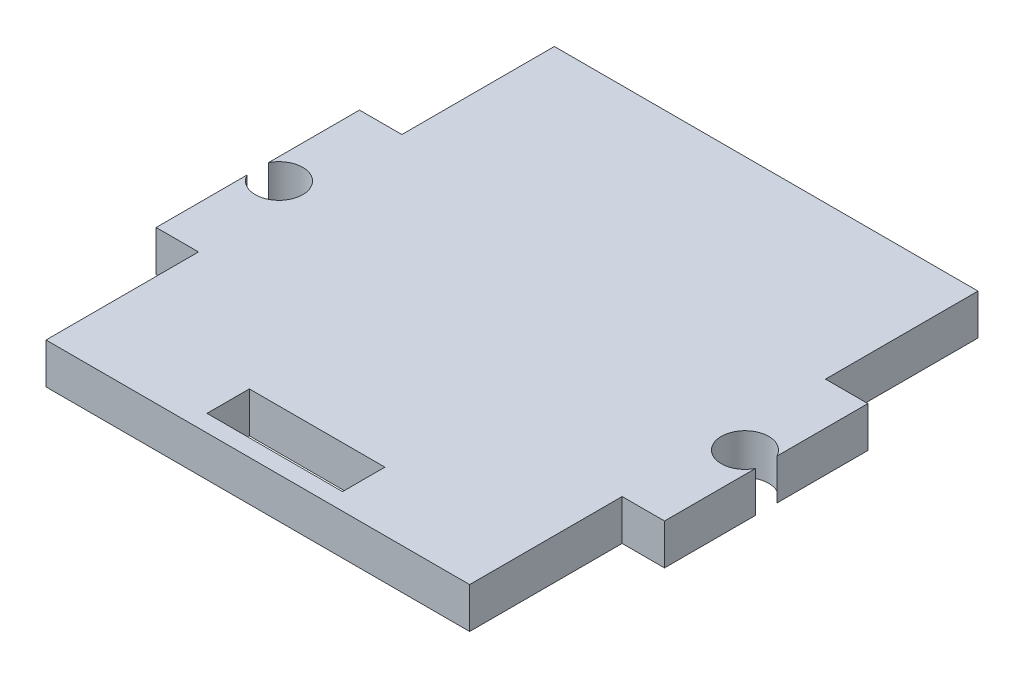
SolidWorks part; units mm, degrees
ref_plane "Front Plane" through (0, 0, 0) normal (0, 0, 1) x (1, 0, 0)
ref_plane "Top Plane" through (0, 0, 0) normal (0, 1, 0) x (1, 0, 0)
ref_plane "Right Plane" through (0, 0, 0) normal (1, 0, 0) x (0, 0, -1)
sketch "Sketch1" plane through (0, 0, 0) normal (0, 1, 0) x (1, 0, 0)
  line L0 (3.175, 38.1) -> (3.175, 26.67)
  line L1 (3.175, 0) -> (34.925, 0)
  line L2 (0, 11.43) -> (0, 18.2493)
  line L3 (3.175, 38.1) -> (34.925, 38.1)
  line L4 (38.1, 11.43) -> (38.1, 18.2493)
  line L5 (3.175, 26.67) -> (0, 26.67)
  line L6 (3.175, 0) -> (3.175, 11.43)
  line L7 (3.175, 11.43) -> (0, 11.43)
  line L8 (19.05, 38.1) -> (19.05, 0) construction
  line L9 (0, 19.05) -> (38.1, 19.05) construction
  line L10 (1.5875, 26.67) -> (1.5875, 11.43) construction
  line L11 (0, 19.8507) -> (0, 26.67)
  line L12 (34.925, 0) -> (34.925, 11.43)
  line L13 (34.925, 38.1) -> (34.925, 26.67)
  line L14 (34.925, 11.43) -> (38.1, 11.43)
  line L15 (34.925, 26.67) -> (38.1, 26.67)
  line L16 (38.1, 19.8507) -> (38.1, 26.67)
  arc A0 (0, 18.2493) -> (0, 19.8507) centre (1.5875, 19.05) ccw
  arc A1 (38.1, 18.2493) -> (38.1, 19.8507) centre (36.5125, 19.05) cw
  dimension "D3" = 3.175
  dimension "D4" = 11.43
  dimension "D5" = 11.43
extrude "Boss-Extrude1" add sketch "Sketch1" along normal blind 3.048 contours L6 L7 L2 A0 L11 L5 L0 L3 L13 L15 L16 A1 L4 L14 L12 L1
sketch "Sketch2" plane through (0, 3.048, 0) normal (0, 1, 0) x (1, 0, 0)
  line L0 (19.05, 38.1) -> (19.05, -6.4452) construction
  line L1 (3.175, 38.1) -> (34.925, 38.1) construction
  line L2 (3.175, 0) -> (34.925, 0) construction
  line L3 (13.97, 4.445) -> (24.13, 4.445)
  line L4 (13.97, 4.445) -> (13.97, 1.27)
  line L5 (13.97, 1.27) -> (24.13, 1.27)
  line L6 (24.13, 4.445) -> (24.13, 1.27)
  dimension "D1" = 5.08
  dimension "D2" = 10.16
  dimension "D3" = 1.27
  dimension "D4" = 3.175
extrude "Cut-Extrude1" cut sketch "Sketch2" against normal through all
